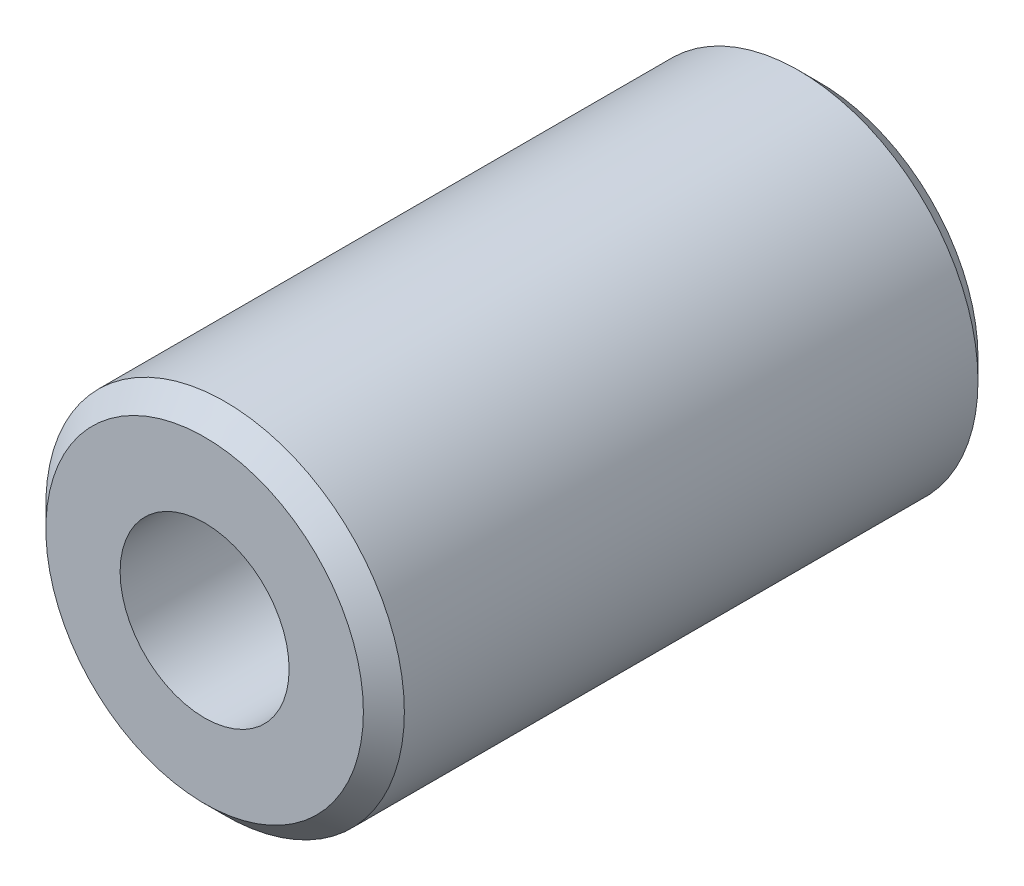
SolidWorks part; units mm, degrees
ref_plane "前视基准面" through (0, 0, 0) normal (0, 0, 1) x (1, 0, 0)
ref_plane "上视基准面" through (0, 0, 0) normal (0, 1, 0) x (1, 0, 0)
ref_plane "右视基准面" through (0, 0, 0) normal (1, 0, 0) x (0, 0, -1)
other "Configuration Table"
sketch "草图1" plane through (0, 0, 0) normal (0, 0, 1) x (1, 0, 0)
  circle A0 centre (0, 0) radius 3.5
  circle A1 centre (0, 0) radius 1.65
  dimension "D1" = 7
  dimension "D2" = 3.3
extrude "凸台-拉伸1" add sketch "草图1" along normal blind 12
chamfer "倒角1" distance 0.4 angle 45 2 edges at (3.5, 0, 12) (3.5, 0, 0)
